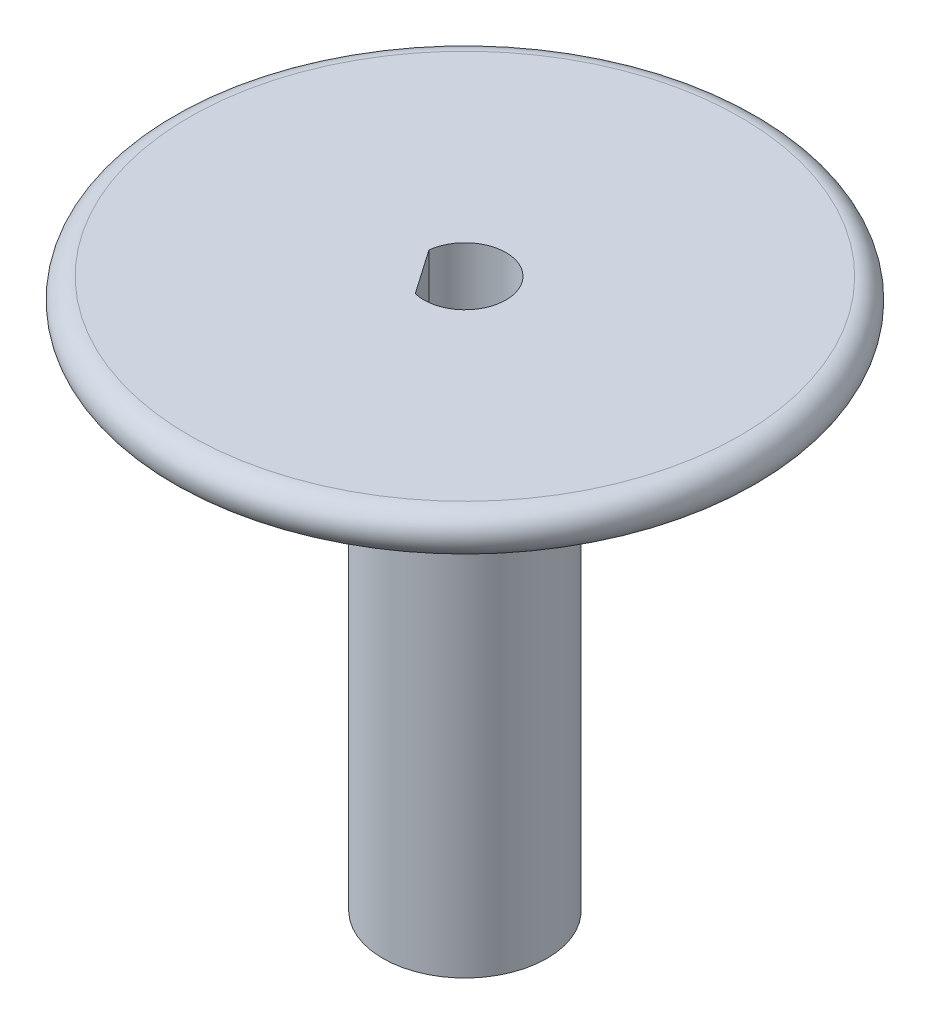
SolidWorks part; units mm, degrees
ref_plane "Front Plane" through (0, 0, 0) normal (0, 0, 1) x (1, 0, 0)
ref_plane "Top Plane" through (0, 0, 0) normal (0, 1, 0) x (1, 0, 0)
ref_plane "Right Plane" through (0, 0, 0) normal (1, 0, 0) x (0, 0, -1)
sketch "Sketch1" plane through (0, 0, 0) normal (0, 0, 1) x (1, 0, 0)
  line L0 (0, -15.7234) -> (0, 18.2634)
  line L1 (0, 18.2634) -> (17.0415, 18.2634)
  line L2 (5.08, 15.7234) -> (17.0415, 15.7234)
  line L5 (5.08, 15.7234) -> (5.08, -15.7234)
  line L6 (5.08, -15.7234) -> (0, -15.7234)
  arc A0 (17.0415, 18.2634) -> (17.0415, 15.7234) centre (17.0415, 16.9934) cw
  point P4 (0, 0)
  dimension "D1" = 2.54
  dimension "D3" = 5.08
revolve "Revolve1" add sketch "Sketch1" angle 360 about L0
sketch "Sketch2" plane through (0, 18.2634, 0) normal (0, 1, 0) x (1, 0, 0)
  line L0 (-0.6047, -2.467) -> (-2.5224, 0.2988)
  arc A0 (-0.6047, -2.467) -> (-2.5224, 0.2988) centre (0, 0) ccw
  dimension "D1" = 3.3655
extrude "Cut-Extrude1" cut sketch "Sketch2" against normal through all
